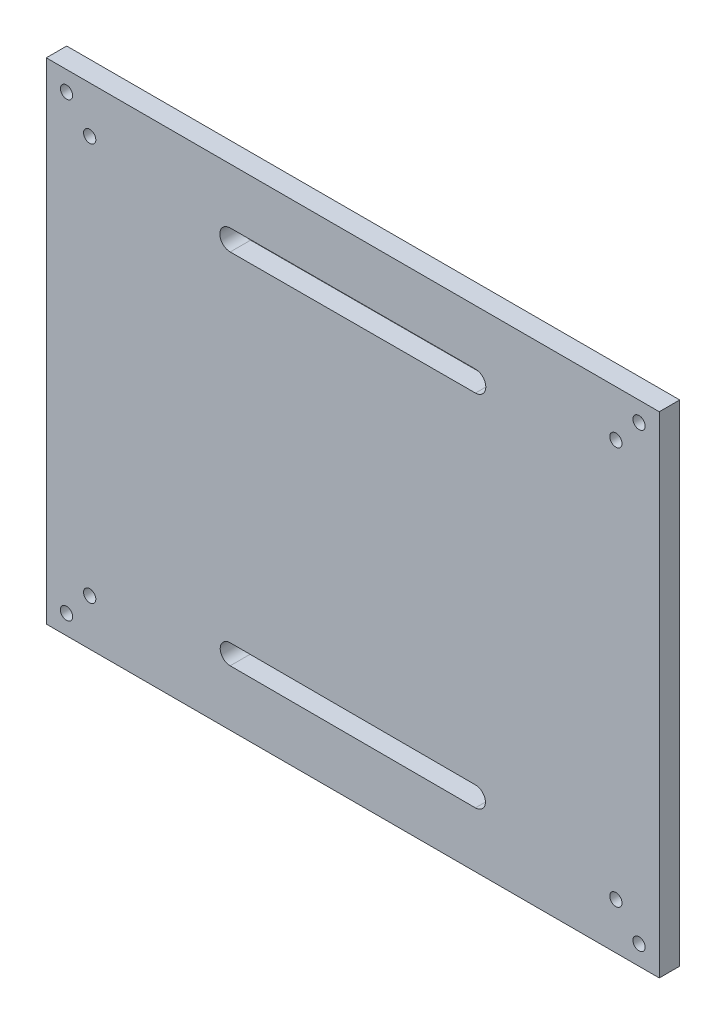
SolidWorks part; units mm, degrees
material "Acrylic (Medium-high impact)"
ref_plane "Front Plane" through (0, 0, 0) normal (0, 0, 1) x (1, 0, 0)
ref_plane "Top Plane" through (0, 0, 0) normal (0, 1, 0) x (1, 0, 0)
ref_plane "Right Plane" through (0, 0, 0) normal (1, 0, 0) x (0, 0, -1)
sketch "Model" plane through (0, 0, 0) normal (0, 0, 1) x (1, 0, 0)
  line L0 (13.9253, 9.5449) -> (163.9253, 9.5449)
  line L1 (163.9253, 9.5449) -> (163.9253, 129.5449)
  line L2 (163.9253, 129.5449) -> (13.9253, 129.5449)
  line L3 (13.9253, 129.5449) -> (13.9253, 9.5449)
  line L4 (58.9257, 115.8414) -> (118.9253, 116.0525)
  line L5 (118.9253, 111.0525) -> (58.9253, 111.0525)
  line L6 (58.9257, 23.2484) -> (118.9253, 23.0373)
  line L7 (118.9253, 28.0373) -> (58.9253, 28.0373)
  circle A0 centre (18.8799, 124.7713) radius 1.5
  circle A1 centre (158.9707, 124.7713) radius 1.5
  circle A2 centre (18.8799, 14.3185) radius 1.5
  circle A3 centre (158.9707, 14.3185) radius 1.5
  circle A4 centre (24.5487, 118.2247) radius 1.5
  circle A5 centre (153.3019, 118.2247) radius 1.5
  circle A6 centre (24.5487, 20.8651) radius 1.5
  circle A7 centre (153.3019, 20.8651) radius 1.5
  arc A8 (118.9253, 111.0525) -> (118.9253, 116.0525) centre (118.9341, 113.5525) ccw
  arc A9 (58.9085, 115.8413) -> (58.9253, 111.0525) centre (58.9253, 113.4469) ccw
  arc A10 (118.9253, 23.0373) -> (118.9253, 28.0373) centre (118.9341, 25.5373) ccw
  arc A11 (58.9253, 28.0373) -> (58.9085, 23.2485) centre (58.9253, 25.6429) ccw
extrude "Boss-Extrude1" add sketch "Model" along normal blind 5
sketch "Sketch2" plane through (0, 0, 0) normal (0, 0, -1) x (-1, 0, 0)
  line L0 (-58.9253, 113.4469) -> (-118.9341, 113.5525) construction
  line L1 (-58.9298, 110.9064) -> (-118.9386, 111.012)
  line L2 (-58.9208, 115.9874) -> (-118.9296, 116.093)
  line L3 (-58.9253, 25.6429) -> (-118.9341, 25.5373) construction
  line L4 (-58.921, 23.2041) -> (-118.9298, 23.0985)
  line L5 (-58.9296, 28.0817) -> (-118.9384, 27.9761)
  arc A0 (-58.9298, 110.9064) -> (-58.9208, 115.9874) centre (-58.9253, 113.4469) ccw
  arc A1 (-118.9296, 116.093) -> (-118.9386, 111.012) centre (-118.9341, 113.5525) ccw
  arc A2 (-58.921, 23.2041) -> (-58.9296, 28.0817) centre (-58.9253, 25.6429) ccw
  arc A3 (-118.9384, 27.9761) -> (-118.9298, 23.0985) centre (-118.9341, 25.5373) ccw
  point P4 (-88.9297, 113.4997)
  point P9 (-88.9297, 25.5901)
extrude "Cut-Extrude1" cut sketch "Sketch2" against normal through all
